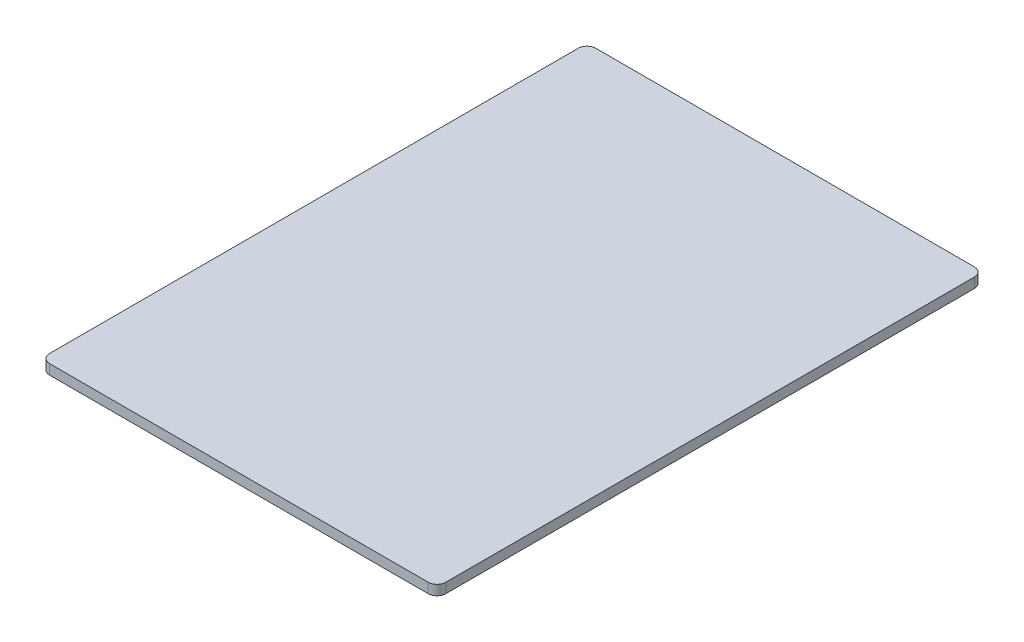
SolidWorks part; units mm, degrees
ref_plane "前视基准面" through (0, 0, 0) normal (0, 0, 1) x (1, 0, 0)
ref_plane "上视基准面" through (0, 0, 0) normal (0, 1, 0) x (1, 0, 0)
ref_plane "右视基准面" through (0, 0, 0) normal (1, 0, 0) x (0, 0, -1)
other "Configuration Table"
sketch "草图1" plane through (0, 0, 0) normal (0, 1, 0) x (1, 0, 0)
  line L1 (-24.0569, 16.5539) -> (20.6631, 16.5539)
  line L2 (-24.0569, 16.5539) -> (-24.0569, -45.0961)
  line L3 (-24.0569, -45.0961) -> (20.6631, -45.0961)
  line L4 (20.6631, 16.5539) -> (20.6631, -45.0961)
  dimension "D1" = 44.72
  dimension "D2" = 61.65
extrude "凸台-拉伸1" add sketch "草图1" along normal blind 1.125
fillet "圆角1" radius 1 4 edges at (-24.0569, 0.5625, 45.0961) (20.6631, 0.5625, 45.0961) (20.6631, 0.5625, -16.5539) (-24.0569, 0.5625, -16.5539)
sketch "草图2" plane through (0, 0, 0) normal (0, -1, 0) x (1, 0, 0)
  line L0 (-23.0569, 45.0961) -> (19.6631, 45.0961) construction
  line L1 (-20.3069, 39.5561) -> (16.9131, 39.5561)
  line L2 (-20.3069, 39.5561) -> (-20.3069, -10.0939)
  line L3 (-20.3069, -10.0939) -> (16.9131, -10.0939)
  line L4 (16.9131, 39.5561) -> (16.9131, -10.0939)
  line L5 (-24.0569, -15.5539) -> (-24.0569, 44.0961) construction
  dimension "D1" = 37.22
  dimension "D2" = 49.65
  dimension "D3" = 5.54
  dimension "D4" = 3.75
extrude "凸台-拉伸2" add sketch "草图2" along normal blind 0.78
